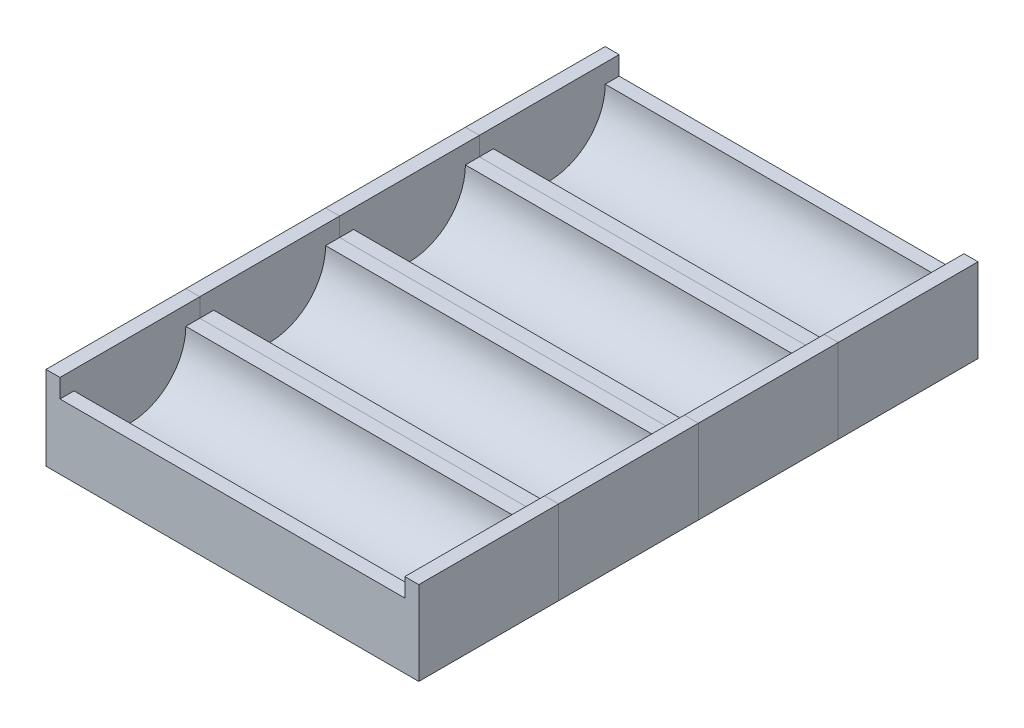
SolidWorks part; units mm, degrees
ref_plane "Front Plane" through (0, 0, 0) normal (0, 0, 1) x (1, 0, 0)
ref_plane "Top Plane" through (0, 0, 0) normal (0, 1, 0) x (1, 0, 0)
ref_plane "Right Plane" through (0, 0, 0) normal (1, 0, 0) x (0, 0, -1)
sketch "Sketch1" plane through (0, 0, 0) normal (1, 0, 0) x (0, 0, -1)
  line L0 (0, 17.7716) -> (0, -15.3442) construction
  line L1 (-15, 3) -> (15, 3)
  line L5 (-15, -15) -> (15, -15)
  line L9 (-15, -12.5) -> (-15, -15)
  line L10 (-15, 3) -> (-15, -12.5)
  line L12 (15, 3) -> (15, -12.5)
  line L14 (15, -12.5) -> (15, -15)
  dimension "D1" = 18
  dimension "D3" = 15
extrude "Boss-Extrude1" add sketch "Sketch1" along normal mid plane 3
sketch "Sketch2" plane through (1.5, 0, 0) normal (1, 0, 0) x (0, 0, -1)
  line L0 (0, 23.8126) -> (0, -26.824) construction
  line L10 (12, -1) -> (15, -1)
  line L14 (-12, -1) -> (-15, -1)
  line L16 (-15, -1) -> (-15, -15)
  line L17 (-15, -15) -> (15, -15)
  line L18 (15, -15) -> (15, -1)
  arc A2 (-12, -1) -> (12, -1) centre (0, -1) ccw
  point P14 (0, -13)
  dimension "D1" = 12
  dimension "D2" = 2
  dimension "D3" = 14
extrude "Boss-Extrude2" add sketch "Sketch2" along normal blind 74
ref_plane "Plane1" through (38.5, 0, 0) normal (1, 0, 0) x (0, 0, -1)
mirror "Mirror1" about plane through (38.5, 0, 0) normal (1, 0, 0) of "Boss-Extrude1"
pattern_linear "LPattern1" count 4 spacing 30 along (0, 0, 1) of bodies 103
